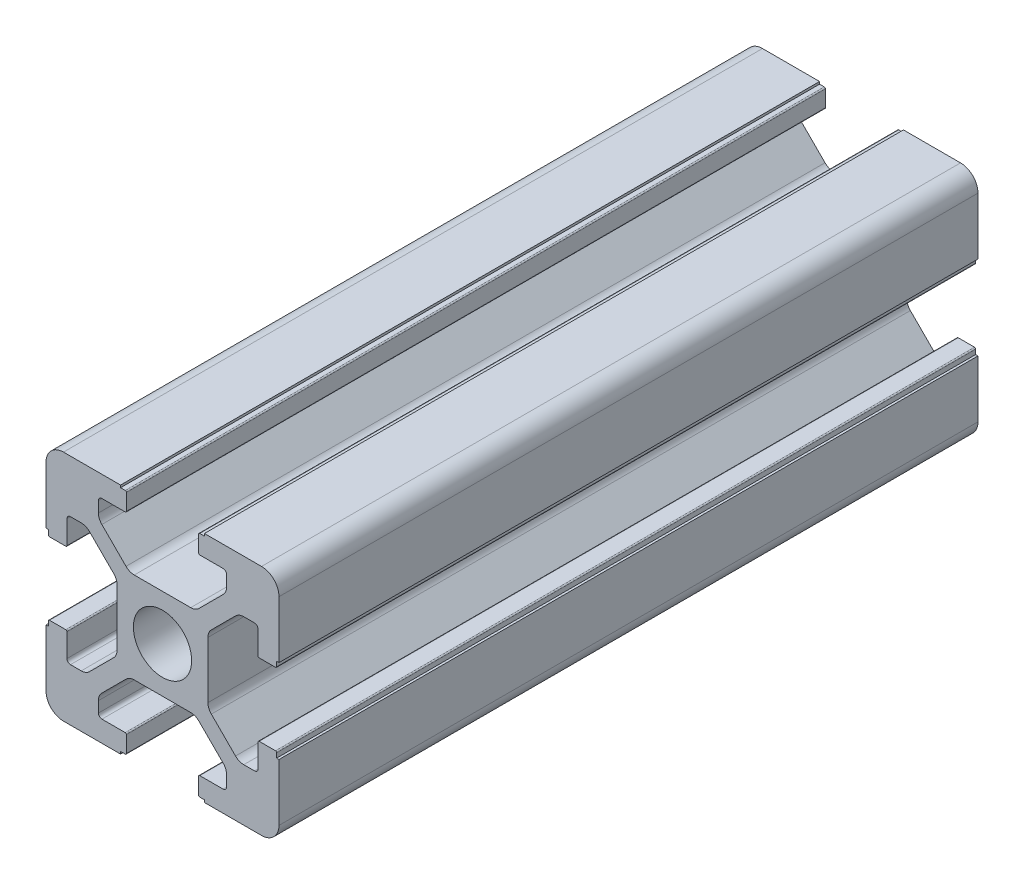
SolidWorks part; units mm, degrees
material "6063-T5"
ref_plane "前视基准面" through (0, 0, 0) normal (0, 0, 1) x (1, 0, 0)
ref_plane "上视基准面" through (0, 0, 0) normal (0, 1, 0) x (1, 0, 0)
ref_plane "右视基准面" through (0, 0, 0) normal (1, 0, 0) x (0, 0, -1)
sketch "草图1" plane through (0, 0, 0) normal (0, 0, 1) x (1, 0, 0)
  line L0 (-1.4389, 10) -> (24.3741, 10) construction
  line L1 (20, 13.6) -> (20, 20)
  line L2 (0, 0) -> (0, 6.4)
  line L3 (0, 20) -> (6.4, 20)
  line L4 (20, 0) -> (20, 6.4)
  line L5 (10, 21.5388) -> (10, -2.4017) construction
  line L6 (6.9, 18.3) -> (6.9, 19.7)
  line L7 (6.8, 18.2) -> (4.8, 18.2)
  line L8 (4.5, 17.9) -> (4.5, 16.9749)
  line L9 (4.7929, 16.2678) -> (6.8678, 14.1929)
  line L10 (7.5749, 13.9) -> (12.4251, 13.9)
  line L11 (6.8, 19.8) -> (6.4, 19.8)
  line L12 (6.4, 19.8) -> (6.4, 20)
  line L13 (0, 13.6) -> (0.2, 13.6)
  line L14 (0.2, 13.6) -> (0.2, 13.2)
  line L15 (0.3, 13.1) -> (1.7, 13.1)
  line L16 (1.8, 13.2) -> (1.8, 15.2)
  line L17 (2.1, 15.5) -> (3.0251, 15.5)
  line L18 (3.7322, 15.2071) -> (5.8071, 13.1322)
  line L19 (6.1, 12.4251) -> (6.1, 7.5749)
  line L20 (13.6, 19.8) -> (13.6, 20)
  line L21 (13.2, 19.8) -> (13.6, 19.8)
  line L22 (13.1, 18.3) -> (13.1, 19.7)
  line L23 (13.2, 18.2) -> (15.2, 18.2)
  line L24 (15.5, 17.9) -> (15.5, 16.9749)
  line L25 (15.2071, 16.2678) -> (13.1322, 14.1929)
  line L26 (0, 6.4) -> (0.2, 6.4)
  line L27 (0.2, 6.4) -> (0.2, 6.8)
  line L28 (0.3, 6.9) -> (1.7, 6.9)
  line L29 (1.8, 6.8) -> (1.8, 4.8)
  line L30 (2.1, 4.5) -> (3.0251, 4.5)
  line L31 (3.7322, 4.7929) -> (5.8071, 6.8678)
  line L32 (13.6, 20) -> (20, 20)
  line L33 (0, 13.6) -> (0, 20)
  line L34 (13.6, 0.2) -> (13.6, 0)
  line L35 (13.2, 0.2) -> (13.6, 0.2)
  line L36 (13.1, 1.7) -> (13.1, 0.3)
  line L37 (13.2, 1.8) -> (15.2, 1.8)
  line L38 (15.5, 2.1) -> (15.5, 3.0251)
  line L39 (15.2071, 3.7322) -> (13.1322, 5.8071)
  line L40 (4.5, 2.1) -> (4.5, 3.0251)
  line L41 (6.8, 1.8) -> (4.8, 1.8)
  line L42 (6.4, 0.2) -> (6.4, 0)
  line L43 (6.8, 0.2) -> (6.4, 0.2)
  line L44 (6.9, 1.7) -> (6.9, 0.3)
  line L45 (4.7929, 3.7322) -> (6.8678, 5.8071)
  line L46 (7.5749, 6.1) -> (12.4251, 6.1)
  line L47 (20, 6.4) -> (19.8, 6.4)
  line L48 (19.8, 6.4) -> (19.8, 6.8)
  line L49 (19.7, 6.9) -> (18.3, 6.9)
  line L50 (18.2, 6.8) -> (18.2, 4.8)
  line L51 (17.9, 4.5) -> (16.9749, 4.5)
  line L52 (16.2678, 4.7929) -> (14.1929, 6.8678)
  line L53 (13.9, 12.4251) -> (13.9, 7.5749)
  line L54 (16.2678, 15.2071) -> (14.1929, 13.1322)
  line L55 (17.9, 15.5) -> (16.9749, 15.5)
  line L56 (18.2, 13.2) -> (18.2, 15.2)
  line L57 (19.7, 13.1) -> (18.3, 13.1)
  line L58 (19.8, 13.6) -> (19.8, 13.2)
  line L59 (20, 13.6) -> (19.8, 13.6)
  line L60 (0, 0) -> (6.4, 0)
  line L61 (13.6, 0) -> (20, 0)
  arc A0 (6.1, 12.4251) -> (5.8071, 13.1322) centre (5.1, 12.4251) ccw
  arc A1 (7.5749, 13.9) -> (6.8678, 14.1929) centre (7.5749, 14.9) cw
  arc A2 (4.5, 16.9749) -> (4.7929, 16.2678) centre (5.5, 16.9749) ccw
  arc A3 (3.7322, 15.2071) -> (3.0251, 15.5) centre (3.0251, 14.5) ccw
  arc A4 (4.5, 17.9) -> (4.8, 18.2) centre (4.8, 17.9) cw
  arc A5 (1.8, 15.2) -> (2.1, 15.5) centre (2.1, 15.2) cw
  arc A6 (0.3, 13.1) -> (0.2, 13.2) centre (0.3, 13.2) cw
  arc A7 (6.9, 19.7) -> (6.8, 19.8) centre (6.8, 19.7) ccw
  arc A8 (1.7, 13.1) -> (1.8, 13.2) centre (1.7, 13.2) ccw
  arc A9 (6.9, 18.3) -> (6.8, 18.2) centre (6.8, 18.3) cw
  arc A10 (13.1, 19.7) -> (13.2, 19.8) centre (13.2, 19.7) cw
  arc A11 (13.1, 18.3) -> (13.2, 18.2) centre (13.2, 18.3) ccw
  arc A12 (15.5, 17.9) -> (15.2, 18.2) centre (15.2, 17.9) ccw
  arc A13 (15.5, 16.9749) -> (15.2071, 16.2678) centre (14.5, 16.9749) cw
  arc A14 (12.4251, 13.9) -> (13.1322, 14.1929) centre (12.4251, 14.9) ccw
  arc A15 (0.3, 6.9) -> (0.2, 6.8) centre (0.3, 6.8) ccw
  arc A16 (1.7, 6.9) -> (1.8, 6.8) centre (1.7, 6.8) cw
  arc A17 (1.8, 4.8) -> (2.1, 4.5) centre (2.1, 4.8) ccw
  arc A18 (3.7322, 4.7929) -> (3.0251, 4.5) centre (3.0251, 5.5) cw
  arc A19 (6.1, 7.5749) -> (5.8071, 6.8678) centre (5.1, 7.5749) cw
  arc A20 (13.1, 0.3) -> (13.2, 0.2) centre (13.2, 0.3) ccw
  arc A21 (13.1, 1.7) -> (13.2, 1.8) centre (13.2, 1.7) cw
  arc A22 (15.5, 2.1) -> (15.2, 1.8) centre (15.2, 2.1) cw
  arc A23 (15.5, 3.0251) -> (15.2071, 3.7322) centre (14.5, 3.0251) ccw
  arc A24 (12.4251, 6.1) -> (13.1322, 5.8071) centre (12.4251, 5.1) cw
  arc A25 (4.5, 2.1) -> (4.8, 1.8) centre (4.8, 2.1) ccw
  arc A26 (6.9, 0.3) -> (6.8, 0.2) centre (6.8, 0.3) cw
  arc A27 (6.9, 1.7) -> (6.8, 1.8) centre (6.8, 1.7) ccw
  arc A28 (4.5, 3.0251) -> (4.7929, 3.7322) centre (5.5, 3.0251) cw
  arc A29 (7.5749, 6.1) -> (6.8678, 5.8071) centre (7.5749, 5.1) ccw
  arc A30 (19.7, 6.9) -> (19.8, 6.8) centre (19.7, 6.8) cw
  arc A31 (18.3, 6.9) -> (18.2, 6.8) centre (18.3, 6.8) ccw
  arc A32 (18.2, 4.8) -> (17.9, 4.5) centre (17.9, 4.8) cw
  arc A33 (16.2678, 4.7929) -> (16.9749, 4.5) centre (16.9749, 5.5) ccw
  arc A34 (13.9, 7.5749) -> (14.1929, 6.8678) centre (14.9, 7.5749) ccw
  arc A35 (13.9, 12.4251) -> (14.1929, 13.1322) centre (14.9, 12.4251) cw
  arc A36 (16.2678, 15.2071) -> (16.9749, 15.5) centre (16.9749, 14.5) cw
  arc A37 (18.2, 15.2) -> (17.9, 15.5) centre (17.9, 15.2) ccw
  arc A38 (18.3, 13.1) -> (18.2, 13.2) centre (18.3, 13.2) cw
  arc A39 (19.7, 13.1) -> (19.8, 13.2) centre (19.7, 13.2) ccw
  circle A40 centre (10, 10) radius 2.5
  point P39 (0.2, 13.1)
  point P42 (6.9, 19.8)
  point P45 (1.8, 13.1)
  point P48 (6.9, 18.2)
  point P66 (10, 13.9)
  point P83 (6.1, 10)
  dimension "D19" = 1
  dimension "D20" = 1
  dimension "D21" = 0.3
  dimension "D22" = 0.1
  dimension "D23" = 5
  dimension "D1" = 20
  dimension "D2" = 20
  dimension "D3" = 10
  dimension "D4" = 10
  dimension "D5" = 1.8
  dimension "D6" = 0.5
  dimension "D7" = 1.6
  dimension "D8" = 3.1
  dimension "D9" = 6.1
  dimension "D10" = 5.5
  dimension "D11" = 3.1
  dimension "D12" = 6.1
  dimension "D13" = 5.5
  dimension "D14" = 1.8
  dimension "D15" = 0.5
  dimension "D16" = 1.5
  dimension "D17" = 45
  dimension "D18" = 1.6
extrude "凸台-拉伸1" add sketch "草图1" along normal blind 60
fillet "圆角1" radius 1.5 4 edges at (20, 0, 30) (0, 0, 30) (0, 20, 30) (20, 20, 30)
